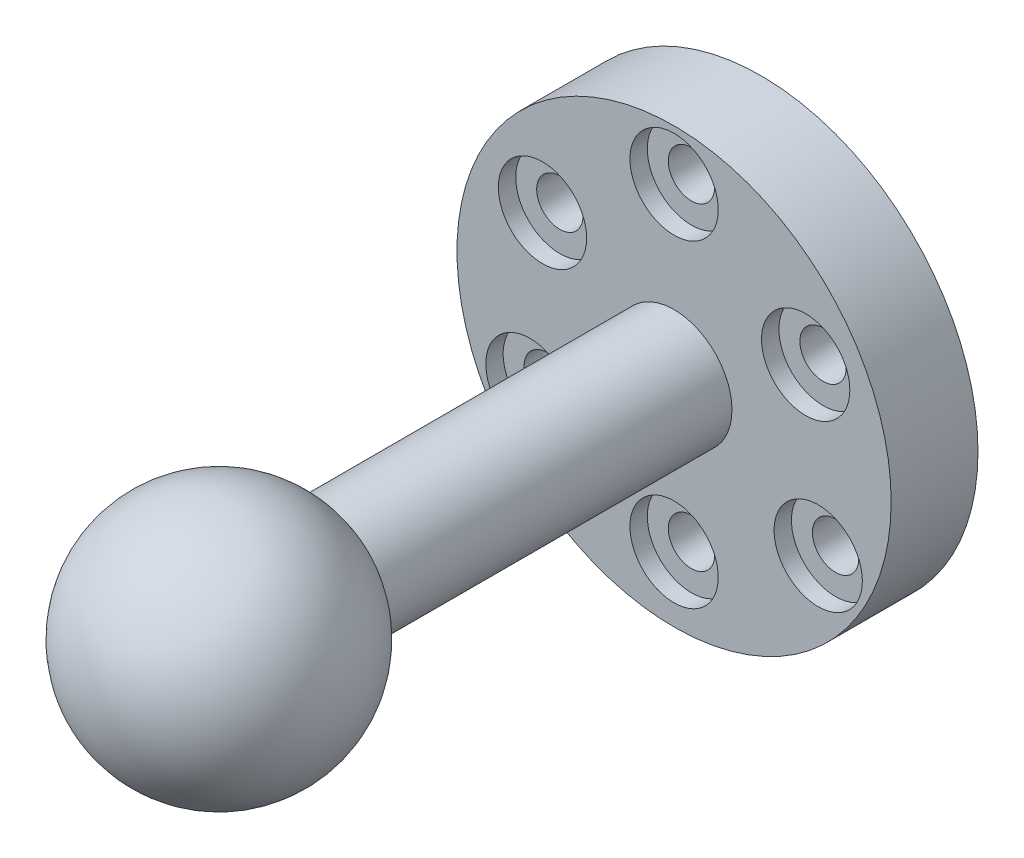
SolidWorks part; units mm, degrees
ref_plane "前视基准面" through (0, 0, 0) normal (0, 0, 1) x (1, 0, 0)
ref_plane "上视基准面" through (0, 0, 0) normal (0, 1, 0) x (1, 0, 0)
ref_plane "右视基准面" through (0, 0, 0) normal (1, 0, 0) x (0, 0, -1)
other "Configuration Table"
sketch "草图1" plane through (0, 0, 0) normal (0, 0, 1) x (1, 0, 0)
  circle A0 centre (0, 0) radius 15
  dimension "D1" = 30
extrude "凸台-拉伸1" add sketch "草图1" along normal blind 6 contours A0
sketch "草图2" plane through (0, 0, 6) normal (0, 0, 1) x (1, 0, 0)
  line L0 (0, 0) -> (0, 11.5) construction
  line L1 (0, 0) -> (-9.0933, 5.25) construction
  circle A0 centre (0, 11.5) radius 1.6
  circle A1 centre (9.9593, -5.75) radius 1.6
  circle A2 centre (-9.9593, -5.75) radius 1.6
  circle A3 centre (-9.0933, 5.25) radius 1.6
  circle A4 centre (9.0933, 5.25) radius 1.6
  circle A5 centre (0, -10.5) radius 1.6
  point P11 (0, 0)
  point P18 (0, 0)
  dimension "D1" = 3.2
  dimension "D5" = 3.2
  dimension "D2" = 11.5
  dimension "D4" = 60
  dimension "D6" = 10.5
  dimension "D3" = 3
  dimension "D7" = 3
extrude "切除-拉伸1" cut sketch "草图2" against normal through all
sketch "草图3" plane through (0, 0, 6) normal (0, 0, 1) x (1, 0, 0)
  circle A0 centre (-9.0933, 5.25) radius 3.05
  circle A1 centre (0, 11.5) radius 3.05
  circle A2 centre (9.0933, 5.25) radius 3.05
  circle A3 centre (9.9593, -5.75) radius 3.05
  circle A4 centre (0, -10.5) radius 3.05
  circle A5 centre (-9.9593, -5.75) radius 3.05
  dimension "D1" = 6.1
extrude "切除-拉伸2" cut sketch "草图3" against normal blind 1.2
sketch "草图4" plane through (0, 0, 6) normal (0, 0, 1) x (1, 0, 0)
  circle A0 centre (0, 0) radius 4
  dimension "D1" = 8
extrude "凸台-拉伸2" add sketch "草图4" along normal blind 25
sketch "草图5" plane through (0, 0, 0) normal (0, 1, 0) x (1, 0, 0)
  line L0 (-4, -31) -> (4, -31) construction
  line L1 (-4, -31) -> (4, -31) construction
  line L2 (0, -37.45) -> (0, -29) construction
  line L3 (0, -29) -> (0, -45.9)
  arc A0 (0, -29) -> (0, -45.9) centre (0, -37.45) ccw
  dimension "D1" = 16.9
  dimension "D2" = 2
sketch "草图6" plane through (0, 0, 0) normal (0, 1, 0) x (1, 0, 0)
  line L0 (0, 0) -> (0, -14.2461) construction
revolve "旋转2" add sketch "草图5" angle 360 about L0
